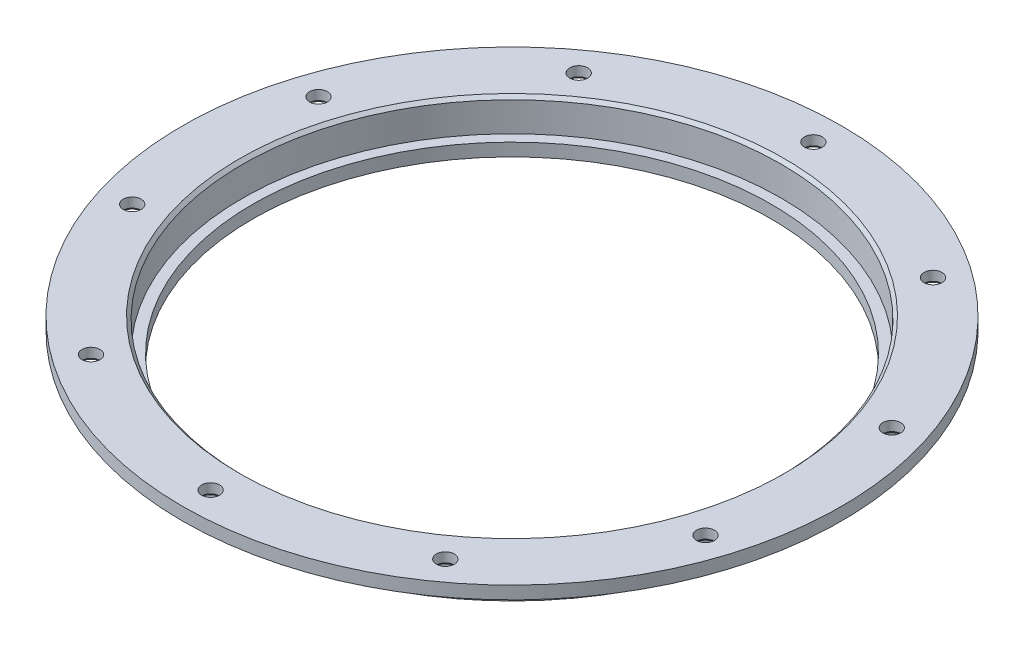
SolidWorks part; units mm, degrees
ref_plane "정면" through (0, 0, 0) normal (0, 0, 1) x (1, 0, 0)
ref_plane "윗면" through (0, 0, 0) normal (0, 1, 0) x (1, 0, 0)
ref_plane "우측면" through (0, 0, 0) normal (1, 0, 0) x (0, 0, -1)
sketch "스케치1" plane through (0, 0, 0) normal (0, 1, 0) x (1, 0, 0)
  circle A0 centre (0, 0) radius 40.5
  circle A1 centre (0, 0) radius 44.5
  dimension "D1" = 81
  dimension "D2" = 4
extrude "보스-돌출1" add sketch "스케치1" along normal blind 2
sketch "스케치2" plane through (0, 2, 0) normal (0, 1, 0) x (1, 0, 0)
  circle A0 centre (0, 0) radius 42.1
  circle A1 centre (0, 0) radius 44.5
  circle A2 centre (0, 0) radius 44.5 construction
  circle A3 centre (0, 0) radius 40.5 construction
  dimension "D1" = 1.6
extrude "보스-돌출2" add sketch "스케치2" along normal blind 3.1
sketch "스케치3" plane through (0, 5.1, 0) normal (0, 1, 0) x (1, 0, 0)
  circle A1 centre (0, 0) radius 51.5
  circle A3 centre (0, 0) radius 44.5 construction
  circle A4 centre (0, 0) radius 42.1
  dimension "D1" = 7
extrude "보스-돌출3" add sketch "스케치3" along normal blind 2
sketch "스케치6" plane through (0, 7.1, 0) normal (0, 1, 0) x (1, 0, 0)
  circle A0 centre (0, 0) radius 47.1 construction
  circle A2 centre (0, 47.1) radius 1.4
  circle A3 centre (27.6847, 38.1047) radius 1.4
  circle A4 centre (44.7948, 14.5547) radius 1.4
  circle A5 centre (44.7948, -14.5547) radius 1.4
  circle A6 centre (27.6847, -38.1047) radius 1.4
  circle A7 centre (0, -47.1) radius 1.4
  circle A8 centre (-27.6847, -38.1047) radius 1.4
  circle A9 centre (-44.7948, -14.5547) radius 1.4
  circle A10 centre (-44.7948, 14.5547) radius 1.4
  circle A11 centre (-27.6847, 38.1047) radius 1.4
  circle A14 centre (0, 0) radius 42.1 construction
  point P31 (0, 0)
  dimension "D1" = 5
  dimension "D2" = 2.8
  dimension "D3" = 10
extrude "컷-돌출3" cut sketch "스케치6" against normal through all
chamfer "모따기1" distance 0.5 angle 45 10 edges at (-44.7948, 5.1, 15.9547) (-44.7948, 5.1, -13.1547) (-27.6847, 5.1, -36.7047) (0, 5.1, -45.7) (-27.6847, 5.1, 39.5047) (27.6847, 5.1, 39.5047) (0, 5.1, 48.5) (27.6847, 5.1, -36.7047) (44.7948, 5.1, 15.9547) (44.7948, 5.1, -13.1547)
chamfer "모따기2" distance 0.5 angle 45 2 edges at (0, 7.1, 42.1) (0, 5.1, 44.5)
